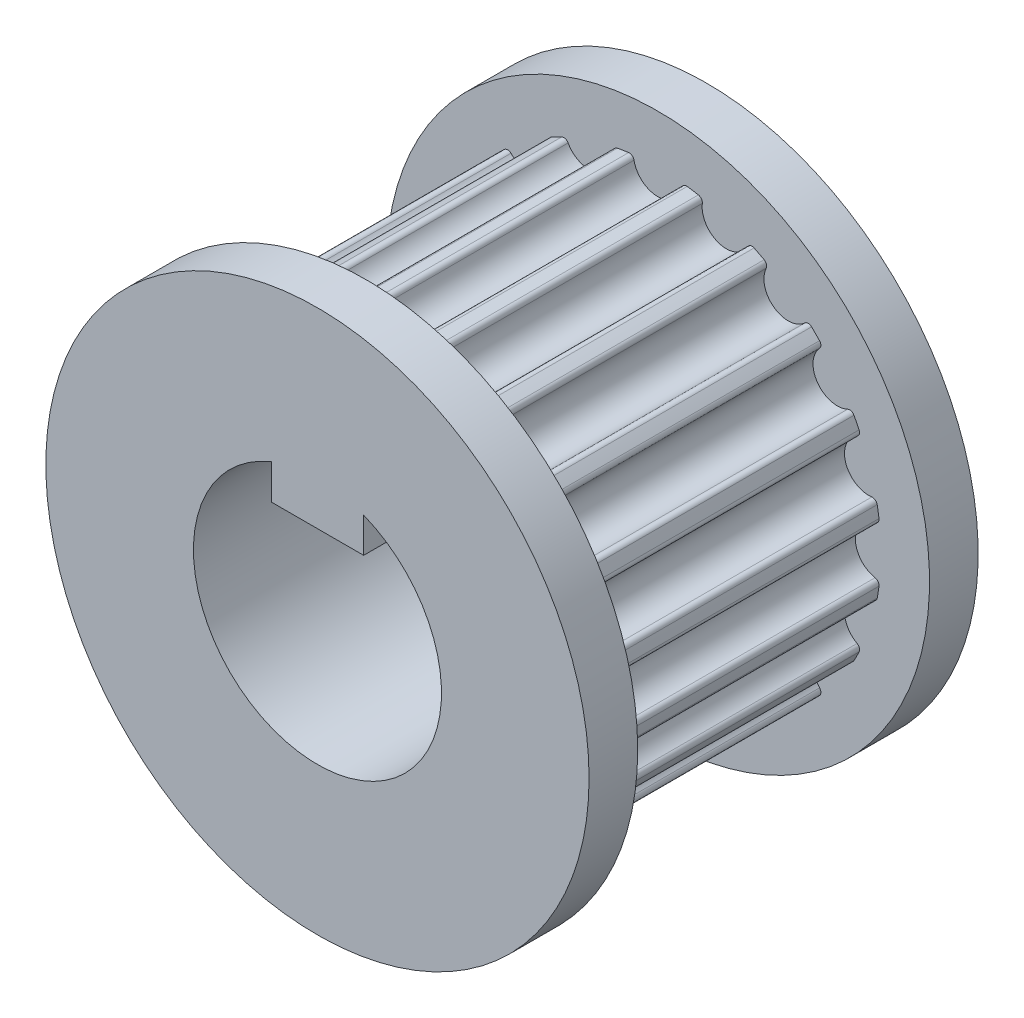
SolidWorks part; units mm, degrees
ref_plane "Front Plane" through (0, 0, 0) normal (0, 0, 1) x (1, 0, 0)
ref_plane "Top Plane" through (0, 0, 0) normal (0, 1, 0) x (1, 0, 0)
ref_plane "Right Plane" through (0, 0, 0) normal (1, 0, 0) x (0, 0, -1)
sketch "Sketch1" plane through (0, 0, 0) normal (0, 0, 1) x (1, 0, 0)
  line L0 (0, 0) -> (0, 9.12) construction
  circle A0 centre (0, 0) radius 9.17
  circle A1 centre (0, 0) radius 9.55 construction
  circle A2 centre (0, 0) radius 7.96 construction
  arc A4 (-1, 9.1153) -> (1, 9.1153) centre (0, 9.12) ccw
  arc A5 (1.8657, 8.9782) -> (3.7678, 8.3602) centre (2.8182, 8.6736) ccw
  arc A6 (4.5488, 7.9622) -> (6.1669, 6.7867) centre (5.3606, 7.3782) ccw
  arc A7 (6.7867, 6.1669) -> (7.9622, 4.5488) centre (7.3782, 5.3606) ccw
  arc A8 (8.3602, 3.7678) -> (8.9782, 1.8657) centre (8.6736, 2.8182) ccw
  arc A9 (9.1153, 1) -> (9.1153, -1) centre (9.12, 0) ccw
  arc A10 (8.9782, -1.8657) -> (8.3602, -3.7678) centre (8.6736, -2.8182) ccw
  arc A11 (7.9622, -4.5488) -> (6.7867, -6.1669) centre (7.3782, -5.3606) ccw
  arc A12 (6.1669, -6.7867) -> (4.5488, -7.9622) centre (5.3606, -7.3782) ccw
  arc A13 (3.7678, -8.3602) -> (1.8657, -8.9782) centre (2.8182, -8.6736) ccw
  arc A14 (1, -9.1153) -> (-1, -9.1153) centre (0, -9.12) ccw
  arc A15 (-1.8657, -8.9782) -> (-3.7678, -8.3602) centre (-2.8182, -8.6736) ccw
  arc A16 (-4.5488, -7.9622) -> (-6.1669, -6.7867) centre (-5.3606, -7.3782) ccw
  arc A17 (-6.7867, -6.1669) -> (-7.9622, -4.5488) centre (-7.3782, -5.3606) ccw
  arc A18 (-8.3602, -3.7678) -> (-8.9782, -1.8657) centre (-8.6736, -2.8182) ccw
  arc A19 (-9.1153, -1) -> (-9.1153, 1) centre (-9.12, 0) ccw
  arc A20 (-8.9782, 1.8657) -> (-8.3602, 3.7678) centre (-8.6736, 2.8182) ccw
  arc A21 (-7.9622, 4.5488) -> (-6.7867, 6.1669) centre (-7.3782, 5.3606) ccw
  arc A22 (-6.1669, 6.7867) -> (-4.5488, 7.9622) centre (-5.3606, 7.3782) ccw
  arc A23 (-3.7678, 8.3602) -> (-1.8657, 8.9782) centre (-2.8182, 8.6736) ccw
  point P6 (0, 9.17)
  point P69 (0, 0)
  dimension "D1" = 18.34
  dimension "D2" = 19.1
  dimension "D3" = 1.21
  dimension "D4" = 0.05
  dimension "D5" = 2
  dimension "D6" = 20
extrude "Boss-Extrude1" add sketch "Sketch1" along normal blind 12 contours A23 A0 A22 A21 A20 A19 A18 A17 A16 A15 A14 A13 A12 A11 A10 A9 A8 A7 A6 A5 A4
sketch "Sketch2" plane through (0, 0, 12) normal (0, 0, 1) x (1, 0, 0)
  circle A0 centre (0, 0) radius 5.1
  dimension "D1" = 10.2
extrude "Cut-Extrude1" cut sketch "Sketch2" against normal through all
fillet "Fillet1" radius 0.2 40 edges at (-3.7678, 8.3602, 6) (-1.8657, 8.9782, 6) (-1, 9.1153, 6) (1, 9.1153, 6) (1.8657, 8.9782, 6) (3.7678, 8.3602, 6) (4.5488, 7.9622, 6) (6.1669, 6.7867, 6) (6.7867, 6.1669, 6) (7.9622, 4.5488, 6) (8.3602, 3.7678, 6) (8.9782, 1.8657, 6) (9.1153, 1, 6) (9.1153, -1, 6) (8.9782, -1.8657, 6) (8.3602, -3.7678, 6) (7.9622, -4.5488, 6) (6.7867, -6.1669, 6) (6.1669, -6.7867, 6) (4.5488, -7.9622, 6) (3.7678, -8.3602, 6) (1.8657, -8.9782, 6) (1, -9.1153, 6) (-1, -9.1153, 6) (-1.8657, -8.9782, 6) (-3.7678, -8.3602, 6) (-4.5488, -7.9622, 6) (-6.1669, -6.7867, 6) (-6.7867, -6.1669, 6) (-7.9622, -4.5488, 6) (-8.3602, -3.7678, 6) (-8.9782, -1.8657, 6) (-9.1153, -1, 6) (-9.1153, 1, 6) (-8.9782, 1.8657, 6) (-8.3602, 3.7678, 6) (-7.9622, 4.5488, 6) (-6.7867, 6.1669, 6) (-6.1669, 6.7867, 6) (-4.5488, 7.9622, 6)
sketch "Sketch4" plane through (0, 0, 12) normal (0, 0, 1) x (1, 0, 0)
  circle A0 centre (0, 0) radius 5.1
  circle A1 centre (0, 0) radius 11.17
  arc A2 (8.2734, 3.9547) -> (8.0624, 4.3689) centre (0, 0) ccw construction
  dimension "D1" = 2
extrude "Boss-Extrude2" add sketch "Sketch4" along normal blind 2
sketch "Sketch6" plane through (0, 0, 0) normal (0, 0, -1) x (-1, 0, 0)
  circle A0 centre (0, 0) radius 5.1
  circle A1 centre (0, 0) radius 11.17
extrude "Boss-Extrude3" add sketch "Sketch6" along normal blind 2
sketch "Sketch8" plane through (0, 0, 14) normal (0, 0, 1) x (1, 0, 0)
  line L1 (-1.9, 6.9) -> (1.9, 6.9)
  line L2 (-1.9, 6.9) -> (-1.9, 3.3)
  line L3 (-1.9, 3.3) -> (1.9, 3.3)
  line L4 (1.9, 6.9) -> (1.9, 3.3)
  line L5 (0, 3.3) -> (0, 6.9) construction
  line L6 (-1.9, 5.1) -> (1.9, 5.1) construction
  circle A0 centre (0, 0) radius 5.1 construction
  point P0 (0, 5.1)
  dimension "D1" = 1.8
  dimension "D2" = 3.8
extrude "Boss-Extrude4" add sketch "Sketch8" against normal up to surface (16 mm away) up to face at (-11.17, 0, -2)
